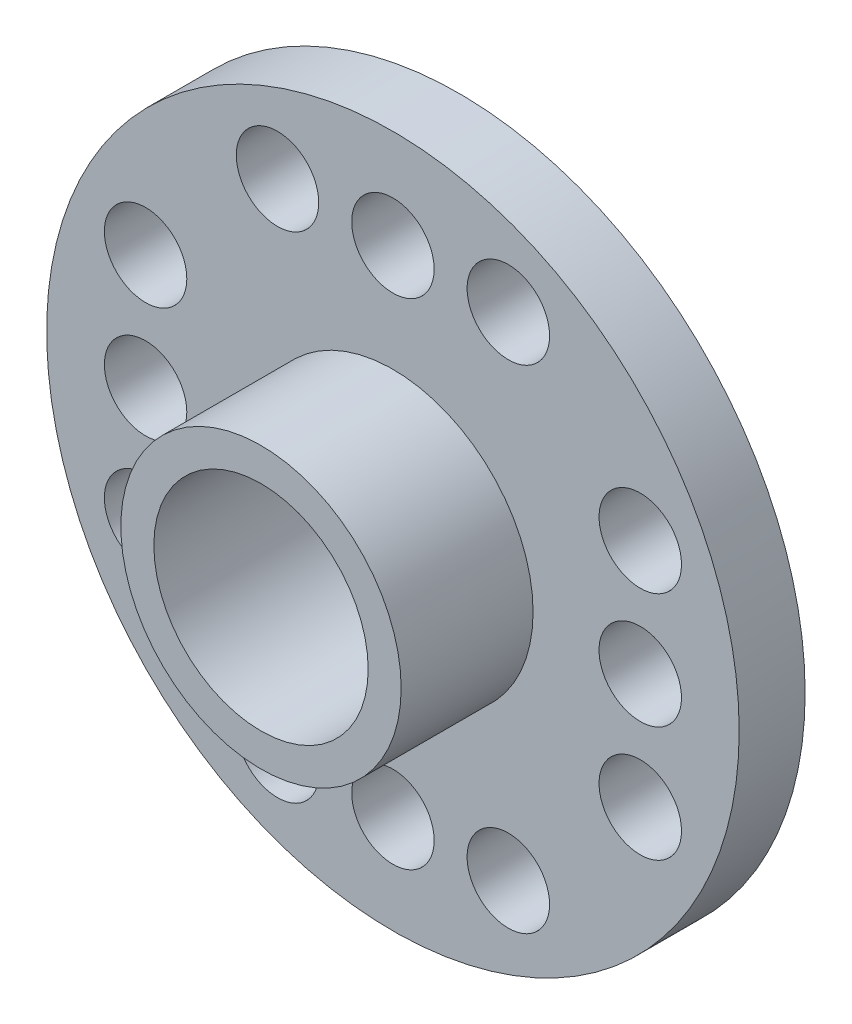
SolidWorks part; units mm, degrees
ref_plane "Front Plane" through (0, 0, 0) normal (0, 0, 1) x (1, 0, 0)
ref_plane "Top Plane" through (0, 0, 0) normal (0, 1, 0) x (1, 0, 0)
ref_plane "Right Plane" through (0, 0, 0) normal (1, 0, 0) x (0, 0, -1)
sketch "Sketch5" plane through (0, 0, 0) normal (0, 0, 1) x (1, 0, 0)
  line L5 (0, 0) -> (0, -7.5) construction
  line L6 (0, -7.5) -> (0, 0) construction
  line L7 (0, 0) -> (7.5, 0) construction
  line L8 (0, 0) -> (0, 7.5) construction
  line L9 (0, 7.5) -> (0, 0) construction
  line L10 (0, 0) -> (-7.5, 0) construction
  line L11 (-7.5, 0) -> (-7.5, -3.5) construction
  line L12 (-7.5, -3.5) -> (-7.5, 0) construction
  line L13 (0, 7.5) -> (-3.5, 7.5) construction
  line L14 (0, 7.5) -> (3.5, 7.5) construction
  line L15 (-7.5, 0) -> (-7.5, 3.5) construction
  line L16 (0, 0) -> (7.5, 0) construction
  line L17 (7.5, 0) -> (7.5, 3.5) construction
  line L18 (-7.5, 0) -> (0, 0) construction
  line L19 (0, 0) -> (0, -7.5) construction
  line L20 (7.5, 0) -> (7.5, -3.5) construction
  line L22 (0, -7.5) -> (-3.5, -7.5) construction
  line L23 (0, 0) -> (0, -7.5) construction
  line L25 (0, -7.5) -> (3.4993, -7.4283) construction
  line L26 (0, 7.5) -> (-3.5, 7.5) construction
  line L27 (0, 7.5) -> (-3.5, 7.5) construction
  circle A0 centre (0, 0) radius 10.5
  circle A1 centre (0, 7.5) radius 1.25
  circle A2 centre (-3.5, 7.5) radius 1.25
  circle A3 centre (3.5, 7.5) radius 1.25
  circle A4 centre (-7.5, 0) radius 1.25
  circle A5 centre (-7.5, 3.5) radius 1.25
  circle A6 centre (-7.5, -3.5) radius 1.25
  circle A7 centre (0, -7.5) radius 1.25
  circle A8 centre (-3.5, -7.5) radius 1.25
  circle A9 centre (3.4993, -7.4283) radius 1.25
  circle A10 centre (7.5, 0) radius 1.25
  circle A11 centre (7.5, 3.5) radius 1.25
  circle A12 centre (7.5, -3.5) radius 1.25
extrude "Boss-Extrude2" add sketch "Sketch5" along normal blind 2
sketch "Sketch6" plane through (0, 0, 0) normal (0, 0, -1) x (-1, 0, 0)
  circle A0 centre (0, 0) radius 1.25
extrude "Cut-Extrude2" cut sketch "Sketch6" against normal blind 2
sketch "Sketch7" plane through (0, 0, 0) normal (0, 0, -1) x (-1, 0, 0)
  circle A0 centre (0, 0) radius 3
extrude "Cut-Extrude3" cut sketch "Sketch7" against normal blind 1
sketch "Sketch9" plane through (0, 0, 0) normal (0, 0, -1) x (-1, 0, 0)
  circle A0 centre (0, 0) radius 3
extrude "Cut-Extrude5" cut sketch "Sketch9" against normal blind 5
sketch "Sketch10" plane through (0, 0, 0) normal (0, 0, -1) x (-1, 0, 0)
  circle A0 centre (0, 0) radius 3
extrude "Boss-Extrude5" add sketch "Sketch10" against normal blind 2
sketch "Sketch11" plane through (0, 0, 0) normal (0, 0, -1) x (-1, 0, 0)
  circle A0 centre (0, 0) radius 3.25
extrude "Cut-Extrude6" cut sketch "Sketch11" against normal blind 2
sketch "Sketch13" plane through (0, 0, 2) normal (0, 0, 1) x (1, 0, 0)
  circle A0 centre (0, 0) radius 3.25
  circle A1 centre (0, 0) radius 4.25
extrude "Boss-Extrude6" add sketch "Sketch13" along normal blind 4
